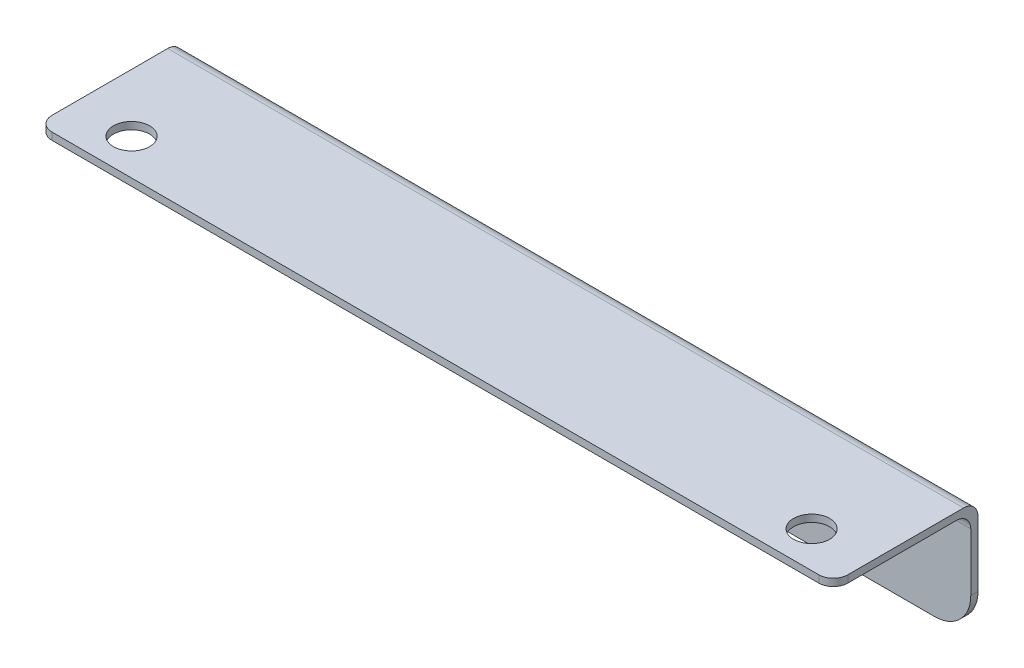
SolidWorks part; units mm, degrees
ref_plane "Front Plane" through (0, 0, 0) normal (0, 0, 1) x (1, 0, 0)
ref_plane "Top Plane" through (0, 0, 0) normal (0, 1, 0) x (1, 0, 0)
ref_plane "Right Plane" through (0, 0, 0) normal (1, 0, 0) x (0, 0, -1)
sketch "Sketch1" plane through (0, 0, 0) normal (0, 0, 1) x (1, 0, 0)
  line L0 (0, 5.1032) -> (0, -23.355) construction
  line L1 (-55, 0) -> (55, 0)
  line L2 (-55, 0) -> (-55, -10)
  line L3 (-50, -15) -> (50, -15)
  line L4 (55, 0) -> (55, -10)
  circle A0 centre (40, -7.5) radius 3
  circle A1 centre (-40, -7.5) radius 3
  arc A2 (50, -15) -> (55, -10) centre (50, -10) ccw
  arc A3 (-50, -15) -> (-55, -10) centre (-50, -10) cw
  point P15 (-55, -15)
  dimension "D4" = 6
  dimension "D5" = 7.5
  dimension "D7" = 5
  dimension "D1" = 110
  dimension "D2" = 55
  dimension "D3" = 15
  dimension "D6" = 40
extrude "Boss-Extrude1" add sketch "Sketch1" along normal blind 1
sketch "Sketch2" plane through (0, 0, 0) normal (0, 1, 0) x (1, 0, 0)
  line L0 (0, 4.9059) -> (0, -25.5119) construction
  line L1 (-55, 0) -> (55, 0)
  line L2 (-55, 0) -> (-55, -20)
  line L3 (-55, -20) -> (55, -20)
  line L4 (55, 0) -> (55, -20)
  circle A0 centre (47, -15) radius 2.5
  circle A1 centre (-47, -15) radius 2.5
  dimension "D2" = 5
  dimension "D1" = 20
  dimension "D3" = 8
  dimension "D4" = 5
extrude "Boss-Extrude2" add sketch "Sketch2" along normal blind 1
fillet "Fillet1" radius 2 4 edges at (0, 1, 0) (55, 0.5, 20) (-55, 0.5, 20)
